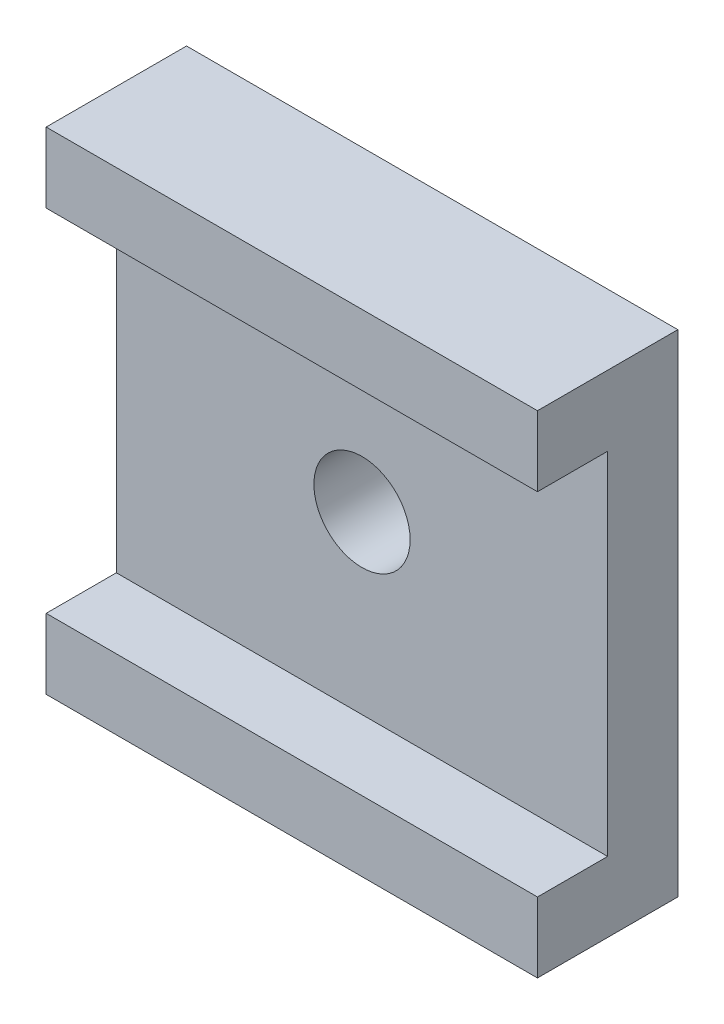
SolidWorks part; units mm, degrees
ref_plane "Front Plane" through (0, 0, 0) normal (0, 0, 1) x (1, 0, 0)
ref_plane "Top Plane" through (0, 0, 0) normal (0, 1, 0) x (1, 0, 0)
ref_plane "Right Plane" through (0, 0, 0) normal (1, 0, 0) x (0, 0, -1)
sketch "Sketch1" plane through (0, 0, 0) normal (0, 0, 1) x (1, 0, 0)
  line L1 (0, 0) -> (70, 0)
  line L2 (0, 0) -> (0, 70)
  line L3 (0, 70) -> (70, 70)
  line L4 (70, 0) -> (70, 70)
  dimension "D1" = 70
  dimension "D2" = 70
extrude "Boss-Extrude1" add sketch "Sketch1" along normal blind 20
sketch "Sketch2" plane through (0, 0, 20) normal (0, 0, 1) x (1, 0, 0)
  line L0 (0, 70) -> (0, 0) construction
  line L1 (0, 10) -> (70, 10)
  line L2 (0, 10) -> (0, 60)
  line L3 (0, 60) -> (70, 60)
  line L4 (70, 10) -> (70, 60)
  line L5 (70, 0) -> (70, 70) construction
  line L6 (0, 0) -> (70, 0) construction
  dimension "D1" = 50
  dimension "D2" = 10
extrude "Cut-Extrude1" cut sketch "Sketch2" against normal blind 10
sketch "Sketch3" plane through (0, 0, 10) normal (0, 0, 1) x (1, 0, 0)
  line L0 (70, 10) -> (70, 60) construction
  line L1 (0, 0) -> (70, 0) construction
  circle A0 centre (35, 35) radius 6.856
  dimension "D1" = 35
  dimension "D2" = 35
extrude "Cut-Extrude2" cut sketch "Sketch3" against normal blind 10
